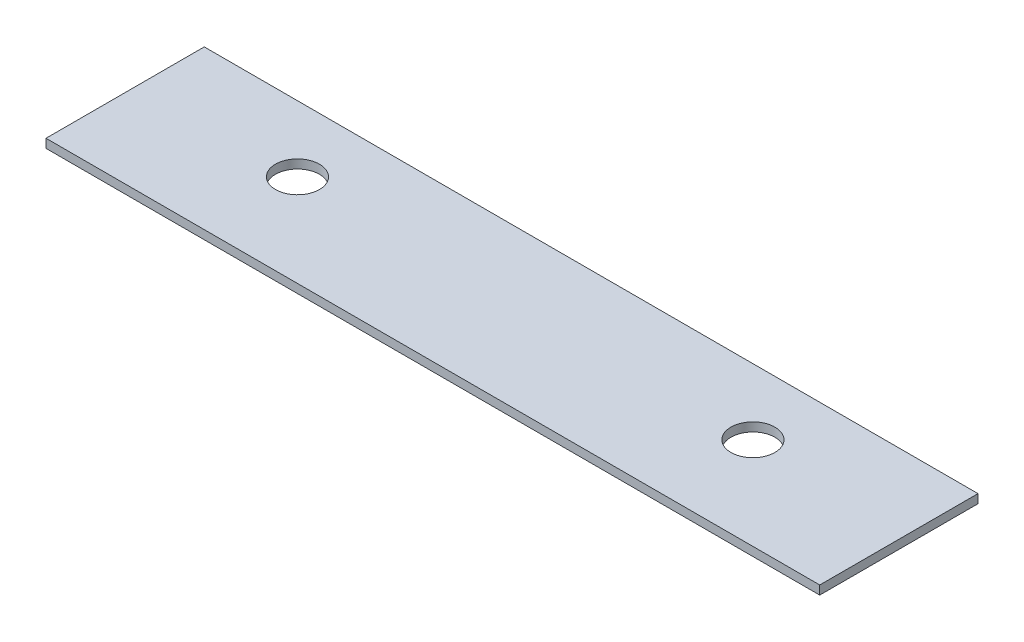
SolidWorks part; units mm, degrees
ref_plane "Alzado" through (0, 0, 0) normal (0, 0, 1) x (1, 0, 0)
ref_plane "Planta" through (0, 0, 0) normal (0, 1, 0) x (1, 0, 0)
ref_plane "Vista lateral" through (0, 0, 0) normal (1, 0, 0) x (0, 0, -1)
sketch "Sketch1" plane through (0, 0, 0) normal (0, 1, 0) x (1, 0, 0)
  line L1 (0.0164, -1.7) -> (88.0164, -1.7)
  line L2 (0.0164, -1.7) -> (0.0164, 16.3)
  line L3 (0.0164, 16.3) -> (88.0164, 16.3)
  line L4 (88.0164, -1.7) -> (88.0164, 16.3)
  line L5 (0.0164, -1.7) -> (88.0164, 16.3) construction
  line L6 (0.0164, 16.3) -> (88.0164, -1.7) construction
  point P4 (44, 8.15)
  dimension "D1" = 88
  dimension "D2" = 18
extrude "Boss-Extrude1" add sketch "Sketch1" along normal blind 1
sketch "Sketch2" plane through (0, 1, 0) normal (0, 1, 0) x (1, 0, 0)
  line L0 (88.0164, -1.7) -> (88.0164, 16.3) construction
  line L1 (88.0164, 16.3) -> (0.0164, 16.3) construction
  line L2 (0.0164, 16.3) -> (0.0164, -1.7) construction
  circle A0 centre (69.9164, 8.8) radius 2.5
  circle A1 centre (18.1164, 8.8) radius 2.5
  dimension "D1" = 5
  dimension "D4" = 5
  dimension "D2" = 18.1
  dimension "D3" = 7.5
  dimension "D5" = 18.1
  dimension "D6" = 7.5
  dimension "D7" = 51.8
extrude "Cut-Extrude1" cut sketch "Sketch2" against normal blind 10
